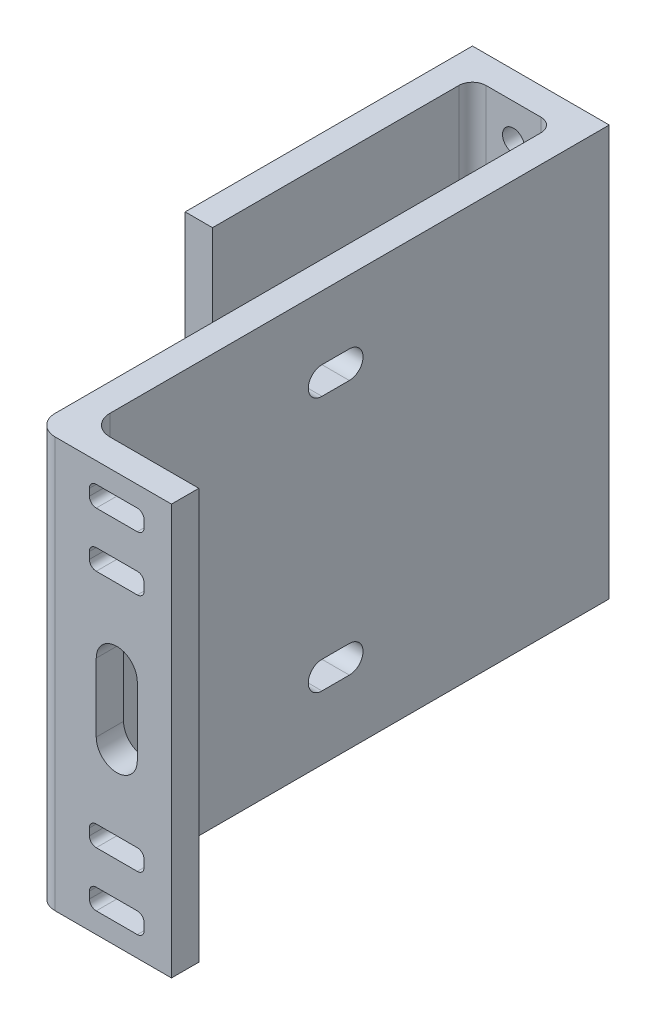
SolidWorks part; units mm, degrees
ref_plane "Top Plane" through (0, 0, 0) normal (0, 0, 1) x (1, 0, 0)
ref_plane "Right Plane" through (0, 0, 0) normal (0, 1, 0) x (1, 0, 0)
ref_plane "Front Plane" through (0, 0, 0) normal (1, 0, 0) x (0, 0, -1)
sketch "Sketch1" plane through (0, 0, 0) normal (0, 1, 0) x (1, 0, 0)
  line L0 (-6, 0) -> (6, 0)
  line L1 (6, 0) -> (6, -76)
  line L2 (-6, 0) -> (-6, -38)
  line L3 (-10, 4) -> (-10, -38)
  line L4 (-10, 4) -> (10, 4)
  line L5 (10, 4) -> (10, -76) construction
  line L6 (-10, -38) -> (-6, -38)
  line L7 (6, -76) -> (10, -76)
  line L8 (10, 4) -> (10, -72)
  line L9 (10, -72) -> (26, -72)
  line L10 (26, -72) -> (26, -76)
  line L11 (26, -76) -> (10, -76)
  line L12 (13.5611, -72) -> (13.5611, -76) construction
  line L13 (-10, -41.81) -> (-6, -41.81) construction
  dimension "D1" = 4
  dimension "D2" = 80
  dimension "D3" = 42
  dimension "D4" = 12
  dimension "D5" = 20
extrude "Boss-Extrude1" add sketch "Sketch1" along normal mid plane 60
sketch "Sketch2" plane through (0, 0, 72) normal (0, 0, -1) x (-1, 0, 0)
  line L0 (-18, -5) -> (-18, 5) construction
  line L1 (-21, -5) -> (-21, 5)
  line L2 (-15, -5) -> (-15, 5)
  line L3 (-26, 0) -> (-10, 0) construction
  line L4 (-26, 30) -> (-26, -30) construction
  line L5 (-10, 30) -> (-10, -30) construction
  line L6 (-26, 30) -> (-10, 30) construction
  line L7 (-22, 27) -> (-14, 27)
  line L8 (-22, 27) -> (-22, 24)
  line L9 (-22, 24) -> (-14, 24)
  line L10 (-14, 27) -> (-14, 24)
  line L11 (-22, 19) -> (-14, 19)
  line L12 (-22, 19) -> (-22, 16)
  line L13 (-22, 16) -> (-14, 16)
  line L14 (-14, 19) -> (-14, 16)
  line L15 (-18, 27) -> (-18, 16) construction
  line L16 (-14, -19) -> (-14, -16)
  line L17 (-22, -16) -> (-14, -16)
  line L18 (-22, -19) -> (-22, -16)
  line L19 (-22, -19) -> (-14, -19)
  line L20 (-14, -27) -> (-14, -24)
  line L21 (-22, -24) -> (-14, -24)
  line L22 (-22, -27) -> (-22, -24)
  line L23 (-22, -27) -> (-14, -27)
  arc A0 (-21, -5) -> (-15, -5) centre (-18, -5) ccw
  arc A1 (-15, 5) -> (-21, 5) centre (-18, 5) ccw
  point P2 (-18, 0)
  point P26 (-13.7207, 14)
  dimension "D1" = 6
  dimension "D2" = 10
  dimension "D3" = 5
  dimension "D4" = 3
  dimension "D5" = 3
  dimension "D6" = 8
extrude "Cut-Extrude1" cut sketch "Sketch2" against normal through all
fillet "Fillet1" radius 1 16 edges at (14, -24, 74) (14, -27, 74) (22, -27, 74) (22, -24, 74) (22, -19, 74) (14, -19, 74) (14, -16, 74) (22, -16, 74) (14, 16, 74) (22, 16, 74) (14, 19, 74) (22, 19, 74) (22, 27, 74) (22, 24, 74) (14, 24, 74) (14, 27, 74)
sketch "Sketch3" plane through (-6, 0, 0) normal (1, 0, 0) x (0, 0, -1)
  line L0 (-72, 30) -> (4, 30) construction
  line L3 (0, 0) -> (-38, 0) construction
  line L7 (0, 30) -> (0, -30) construction
  line L8 (-38, 30) -> (-38, -30) construction
  line L9 (-19, 30) -> (-19, -30) construction
  line L10 (-33.6, -2) -> (-33.6, 2) construction
  line L11 (-35.6, -2) -> (-35.6, 2)
  line L12 (-31.6, -2) -> (-31.6, 2)
  line L13 (-4.4, -2) -> (-4.4, 2) construction
  line L14 (-2.4, -2) -> (-2.4, 2)
  line L15 (-6.4, -2) -> (-6.4, 2)
  arc A4 (-35.6, -2) -> (-31.6, -2) centre (-33.6, -2) ccw
  arc A5 (-31.6, 2) -> (-35.6, 2) centre (-33.6, 2) ccw
  arc A6 (-2.4, -2) -> (-6.4, -2) centre (-4.4, -2) cw
  arc A7 (-6.4, 2) -> (-2.4, 2) centre (-4.4, 2) cw
  point P0 (-5.4, 3.3339)
  point P17 (-19, 0)
  point P25 (-33.6, 0)
  point P33 (-4.4, 0)
  dimension "D1" = 4
  dimension "D2" = 4
  dimension "D3" = 25.2
extrude "Cut-Extrude2" cut sketch "Sketch3" against normal up to next
sketch "Sketch4" plane through (10, 0, 0) normal (1, 0, 0) x (0, 0, -1)
  line L0 (-38, 18.65) -> (-34, 18.65) construction
  line L1 (-38, 20.65) -> (-34, 20.65)
  line L2 (-38, 16.65) -> (-34, 16.65)
  line L3 (-72, 0) -> (0, 0) construction
  line L4 (-38, -18.65) -> (-34, -18.65) construction
  line L5 (-38, -20.65) -> (-34, -20.65)
  line L6 (-38, -16.65) -> (-34, -16.65)
  line L7 (-36, 0) -> (-36, 18.65) construction
  line L8 (-72, 30) -> (-72, -30) construction
  arc A0 (-38, 20.65) -> (-38, 16.65) centre (-38, 18.65) ccw
  arc A1 (-34, 16.65) -> (-34, 20.65) centre (-34, 18.65) ccw
  arc A2 (-38, -20.65) -> (-38, -16.65) centre (-38, -18.65) cw
  arc A3 (-34, -16.65) -> (-34, -20.65) centre (-34, -18.65) cw
  point P2 (-36, 18.65)
  point P12 (-36, -18.65)
  point P19 (-42.9883, 18.75)
  point P20 (0, 0)
  point P21 (-72, 0)
  dimension "D1" = 33.3
  dimension "D2" = 4
  dimension "D3" = 4
extrude "Cut-Extrude3" cut sketch "Sketch4" against normal up to next
sketch "Sketch5" plane through (0, 0, 0) normal (0, 0, 1) x (1, 0, 0)
  line L0 (-6, 0) -> (6, 0) construction
  line L1 (-6, 30) -> (-6, -30) construction
  line L2 (6, 30) -> (6, -30) construction
  circle A0 centre (0, 25) radius 1.6
  circle A1 centre (0, -25) radius 1.6
  point P10 (0, 0)
  dimension "D1" = 3.2
  dimension "D2" = 50
extrude "Cut-Extrude4" cut sketch "Sketch5" against normal through all
fillet "Fillet2" radius 2 2 edges at (6, 0, 0) (-6, 0, 0)
fillet "Fillet3" radius 3 2 edges at (10, 0, 72) (6, 0, 76)
